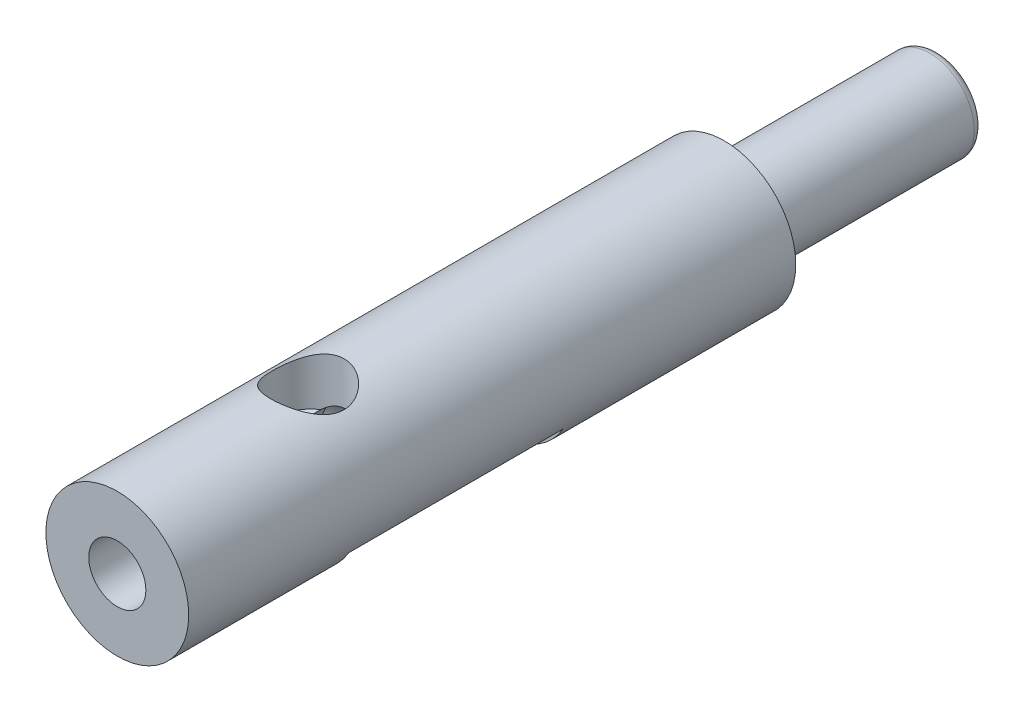
SolidWorks part; units mm, degrees
ref_plane "Front Plane" through (0, 0, 0) normal (0, 0, 1) x (1, 0, 0)
ref_plane "Top Plane" through (0, 0, 0) normal (0, 1, 0) x (1, 0, 0)
ref_plane "Right Plane" through (0, 0, 0) normal (1, 0, 0) x (0, 0, -1)
sketch "Sketch1" plane through (0, 0, 0) normal (0, 0, 1) x (1, 0, 0)
  circle A0 centre (0, 0) radius 2.5
  dimension "D1" = 5
extrude "Boss-Extrude1" add sketch "Sketch1" against normal blind 12
sketch "Sketch2" plane through (0, 0, 0) normal (0, 0, 1) x (1, 0, 0)
  circle A0 centre (0, 0) radius 4
extrude "Boss-Extrude2" add sketch "Sketch2" along normal blind 34
hole_wizard "Ø3.2 (3.2) Diameter Hole1" positions "Sketch4" profile "Sketch5" hole size "Ø3.2" standard "ISO"
sketch "Sketch4" plane through (0, 0, 34) normal (0, 0, 1) x (1, 0, 0)
  point P0 (0, 0)
sketch "Sketch5" plane through (0, 0, 34) normal (1, 0, 0) x (0, -1, 0)
  line L0 (0, 0) -> (0, 14)
  line L1 (0, 14) -> (1.6, 13.0386)
  line L2 (1.6, 13.0386) -> (1.6, 0)
  line L5 (1.6, 0) -> (0, 0)
  line L10 (0, 14) -> (-1.6, 13.0386) construction
  line L11 (0, -6.35) -> (0, 107.95) construction
  dimension "Hole Dia." = 3.2
  dimension "Hole Depth" = 14
  dimension "Drill Angle" = 118
sketch "Sketch6" plane through (0, 0, 0) normal (1, 0, 0) x (0, 0, -1)
  line L0 (-34, -4) -> (-24.5, -4)
  line L1 (-34, -4) -> (0, -4) construction
  line L2 (-24.5, -4) -> (-24.5, -2)
  line L3 (-24.5, -2) -> (-12.5, -2)
  line L4 (-12.5, -2) -> (-12.5, -4)
  line L5 (-34, 4) -> (-22.5, 4)
  line L6 (0, 4) -> (-34, 4) construction
  line L7 (-24.5, -4) -> (-12.5, -4)
  dimension "D1" = 9.5
  dimension "D2" = 2
  dimension "D3" = 12
  dimension "D4" = 11.5
extrude "Cut-Extrude1" cut sketch "Sketch6" against normal through all both and the other way through all contours L2 L7 L4 L3
hole_wizard "Ø4.0 (4) Diameter Hole3" positions "3DSketch4" profile "Sketch13" hole size "Ø4.0" standard "ISO"
sketch3d "3DSketch4"
  circle A0 centre (0, 0, 34) radius 4 construction
  point P0 (-0.1016, 3.9987, 23.2181)
  point P3 (0, 0, 38)
  dimension "D1" = 11.5
sketch "Sketch13" plane through (-0.1016, 3.9987, 23.2181) normal (0, 0, 1) x (-0.9997, -0.0254, 0)
  line L0 (0, 0) -> (0, 4)
  line L1 (0, 4) -> (2, 2.7983)
  line L2 (2, 2.7983) -> (2, 0)
  line L5 (2, 0) -> (0, 0)
  line L10 (0, 4) -> (-2, 2.7983) construction
  line L11 (0, -6.35) -> (0, 107.95) construction
  dimension "Hole Dia." = 4
  dimension "Hole Depth" = 4
  dimension "Drill Angle" = 118
fillet "Fillet1" radius 0.5 1 edges at (2.5, 0, -12)
